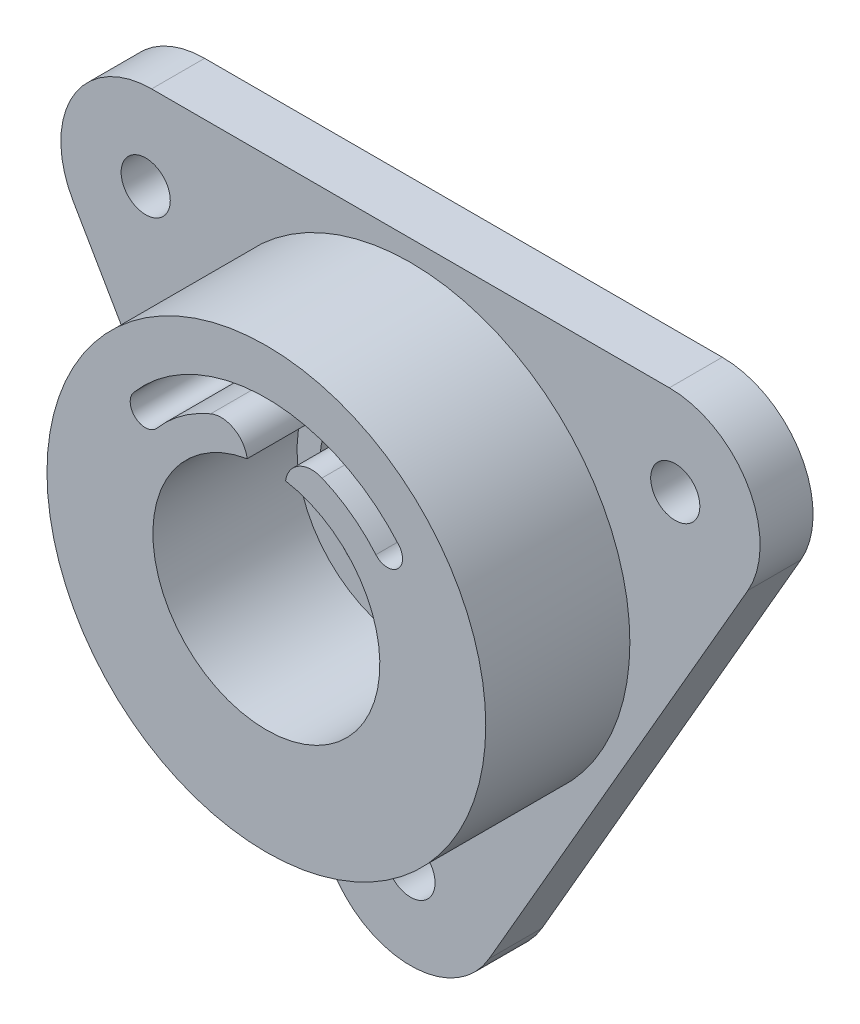
SolidWorks part; units mm, degrees
ref_plane "Plan de face" through (0, 0, 0) normal (0, 0, 1) x (1, 0, 0)
ref_plane "Plan de dessus" through (0, 0, 0) normal (0, 1, 0) x (1, 0, 0)
ref_plane "Plan de droite" through (0, 0, 0) normal (1, 0, 0) x (0, 0, -1)
sketch "Esquisse2" plane through (0, 0, 0) normal (0, 0, 1) x (1, 0, 0)
  circle A0 centre (0, 0) radius 7.5
  circle A1 centre (0, 0) radius 4
  dimension "D1" = 15
  dimension "D2" = 8
sketch "Esquisse1" plane through (0, 0, 0) normal (0, 0, 1) x (1, 0, 0)
  line L0 (-17.5, 10.1036) -> (0, -20.2073) construction
  line L1 (0, -20.2073) -> (17.5, 10.1036) construction
  line L2 (17.5, 10.1036) -> (-17.5, 10.1036) construction
  line L3 (16.0524, 9.2678) -> (-8.4583, -4.8834) construction
  line L4 (0.0575, -0.0332) -> (-30.6383, 17.689) construction
  circle A0 centre (-17.5, 10.1036) radius 1.625
  circle A1 centre (0, -20.2073) radius 1.625
  circle A2 centre (17.5, 10.1036) radius 1.625
  dimension "D2" = 3.25
  dimension "D1" = 35
sketch "Esquisse3" plane through (0, 0, 0) normal (0, 0, 1) x (1, 0, 0)
  line L0 (0, -31.7543) -> (-27.5, 15.8771)
  line L1 (0.0575, -0.0332) -> (-30.6383, 17.689) construction
  line L2 (-27.5, 15.8771) -> (27.5, 15.8771)
  line L3 (16.0524, 9.2678) -> (-8.4583, -4.8834) construction
  line L4 (27.5, 15.8771) -> (0, -31.7543)
  circle A0 centre (-17.5, 10.1036) radius 1.625
  circle A1 centre (17.5, 10.1036) radius 1.625
  circle A2 centre (0, -20.2073) radius 1.625
  circle A3 centre (0, -20.2073) radius 1.625 construction
  circle A4 centre (17.5, 10.1036) radius 1.625 construction
  circle A5 centre (-17.5, 10.1036) radius 1.625 construction
  circle A10 centre (0, 0) radius 6
  circle A13 centre (0, 0) radius 4 construction
  dimension "D2" = 2
  dimension "D1" = 55
extrude "Boss.-Extru.1" add sketch "Esquisse3" along normal blind 3.5
sketch "Esquisse4" plane through (0, 0, 3.5) normal (0, 0, 1) x (1, 0, 0)
  circle A3 centre (0, 0) radius 14.5
  circle A4 centre (0, 0) radius 7.5
  circle A5 centre (0, 0) radius 7.5 construction
  dimension "D1" = 7
extrude "Boss.-Extru.2" add sketch "Esquisse4" along normal blind 9.525
fillet "Congé3" radius 6 3 edges at (27.5, 15.8771, 1.75) (-27.5, 15.8771, 1.75) (0, -31.7543, 1.75)
sketch "Esquisse5" plane through (0, 0, 13.025) normal (0, 0, 1) x (1, 0, 0)
  arc A2 (-7.2381, 6.153) -> (7.2381, 6.153) centre (0, 0) cw
  arc A3 (7.2381, 6.153) -> (8.7619, 7.4484) centre (8, 6.8007) ccw
  arc A4 (8.7619, 7.4484) -> (-8.7619, 7.4484) centre (0, 0) ccw
  arc A5 (-8.7619, 7.4484) -> (-7.2381, 6.153) centre (-8, 6.8007) ccw
  circle A6 centre (0, 0) radius 14.5 construction
  circle A7 centre (0, 0) radius 14.5 construction
  circle A8 centre (0, 0) radius 7.5 construction
  point P8 (0, 9.5)
  dimension "D1" = 3
  dimension "D2" = 2
  dimension "D3" = 16
extrude "Enlèv. mat.-Extru.1" cut sketch "Esquisse5" against normal through all
sketch "Esquisse6" plane through (0, 0, 13.025) normal (0, 0, 1) x (1, 0, 0)
  line L0 (-8.0864, 7.1458) -> (8.0864, 7.1458) construction
  arc A0 (-2.3226, 5.5322) -> (-3.6774, 8.7594) centre (-3, 7.1458) ccw
  circle A1 centre (0, 0) radius 6 construction
  arc A2 (7.2381, 6.153) -> (-7.2381, 6.153) centre (0, 0) ccw construction
  arc A3 (3.6774, 8.7594) -> (2.3226, 5.5322) centre (3, 7.1458) ccw
  arc A5 (3.6774, 8.7594) -> (-3.6774, 8.7594) centre (0, 0) ccw
  arc A6 (2.3226, 5.5322) -> (-2.3226, 5.5322) centre (0, 0) ccw
  point P9 (0, 7.1458)
  dimension "D1" = 6
extrude "Enlèv. mat.-Extru.2" cut sketch "Esquisse6" against normal through all
